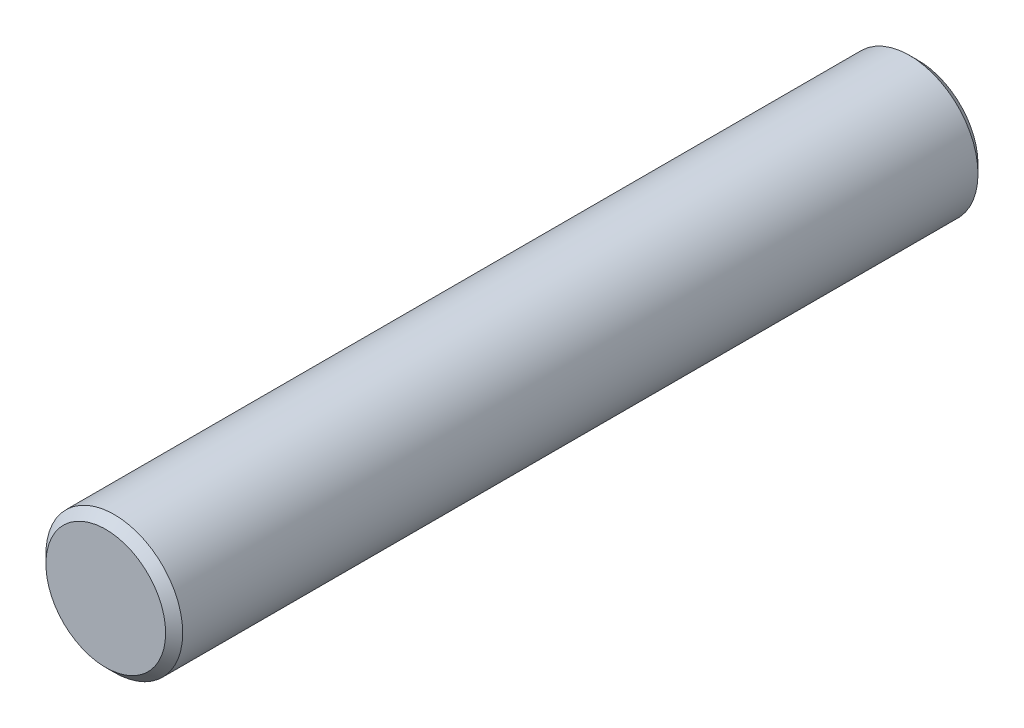
SolidWorks part; units mm, degrees
ref_plane "Front Plane" through (0, 0, 0) normal (0, 0, 1) x (1, 0, 0)
ref_plane "Top Plane" through (0, 0, 0) normal (0, 1, 0) x (1, 0, 0)
ref_plane "Right Plane" through (0, 0, 0) normal (1, 0, 0) x (0, 0, -1)
sketch "Sketch1" plane through (0, 0, 0) normal (0, 0, 1) x (1, 0, 0)
  circle A0 centre (0, 0) radius 4
  dimension "D1" = 8
extrude "Boss-Extrude1" add sketch "Sketch1" along normal blind 47.5
chamfer "Chamfer1" distance 0.5 angle 45 2 edges at (4, 0, 0) (4, 0, 47.5)
